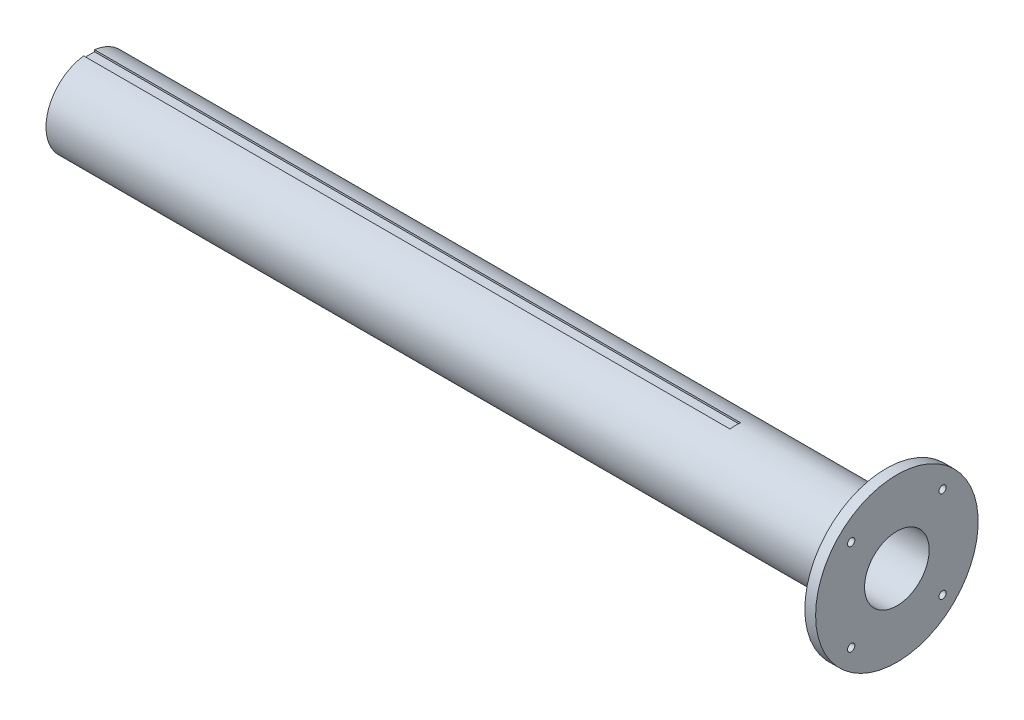
SolidWorks part; units mm, degrees
material "AISI 304"
ref_plane "前视基准面" through (0, 0, 0) normal (0, 0, 1) x (1, 0, 0)
ref_plane "上视基准面" through (0, 0, 0) normal (0, 1, 0) x (1, 0, 0)
ref_plane "右视基准面" through (0, 0, 0) normal (1, 0, 0) x (0, 0, -1)
sketch "Sketch1" plane through (0, 0, 0) normal (0, 0, 1) x (1, 0, 0)
  line L0 (-108.2712, 10) -> (-108.2712, 0)
  line L3 (-108.2712, 0) -> (631.7288, 0)
  line L4 (631.7288, 0) -> (631.7288, -35.4626)
  line L5 (631.7288, -35.4626) -> (641.7288, -35.4626)
  line L6 (641.7288, -35.4626) -> (641.7288, 10)
  line L7 (641.7288, 10) -> (-108.2712, 10)
  line L8 (-148.4581, 40) -> (137.0044, 40) construction
  dimension "D1" = 40
  dimension "D2" = 10
  dimension "D3" = 750
  dimension "D5" = 10
revolve "Revolve1" add sketch "Sketch1" angle 360 about L8
sketch "Sketch2" plane through (-108.2712, 0, 0) normal (-1, 0, 0) x (0, 0, 1)
  line L0 (0, 80) -> (0, 0) construction
  line L2 (-5, 82) -> (5, 82)
  line L3 (-5, 82) -> (-5, 78)
  line L4 (-5, 78) -> (5, 78)
  line L5 (5, 82) -> (5, 78)
  line L6 (-5, 82) -> (5, 78) construction
  line L7 (-5, 78) -> (5, 82) construction
  circle A0 centre (0, 40) radius 40 construction
  circle A1 centre (0, 40) radius 40 construction
  dimension "D1" = 4
  dimension "D2" = 10
extrude "Extrude1" cut sketch "Sketch2" against normal blind 600
sketch "Sketch3" plane through (641.7288, 0, 0) normal (1, 0, 0) x (0, 0, -1)
  line L1 (42.4264, -2.4264) -> (-42.4264, -2.4264) construction
  line L2 (42.4264, -2.4264) -> (42.4264, 82.4264) construction
  line L3 (42.4264, 82.4264) -> (-42.4264, 82.4264) construction
  line L4 (-42.4264, -2.4264) -> (-42.4264, 82.4264) construction
  line L5 (42.4264, -2.4264) -> (-42.4264, 82.4264) construction
  line L6 (42.4264, 82.4264) -> (-42.4264, -2.4264) construction
  circle A0 centre (0, 40) radius 60 construction
  dimension "D1" = 120
hole_wizard "M8 Tapped Hole1" positions "3DSketch1" profile "Sketch4" tap size "M8" standard "GB"
sketch3d "3DSketch1"
  point P0 (641.7288, 82.4264, 42.4264)
  point P3 (641.7288, 82.4264, -42.4264)
  point P6 (641.7288, -2.4264, -42.4264)
  point P9 (641.7288, -2.4264, 42.4264)
sketch "Sketch4" plane through (641.7288, 82.4264, 42.4264) normal (0, 1, 0) x (0, 0, -1)
  line L0 (0, 0) -> (0, 21.7929)
  line L1 (0, 21.7929) -> (3.4, 19.75)
  line L2 (3.4, 19.75) -> (3.4, 0)
  line L5 (3.4, 0) -> (0, 0)
  line L10 (0, 21.7929) -> (-3.4, 19.75) construction
  line L11 (0, -6.35) -> (0, 107.95) construction
  dimension "螺纹孔钻头直径" = 6.8
  dimension "螺纹孔钻头深度" = 19.75
  dimension "导头角度" = 118
cosmetic thread "Cosmetic Thread1" parameters "D1"=10, "D2"=8
cosmetic thread "Cosmetic Thread2" parameters "D1"=10, "D2"=8
cosmetic thread "Cosmetic Thread3" parameters "D1"=10, "D2"=8
cosmetic thread "Cosmetic Thread4" parameters "D1"=10, "D2"=8
